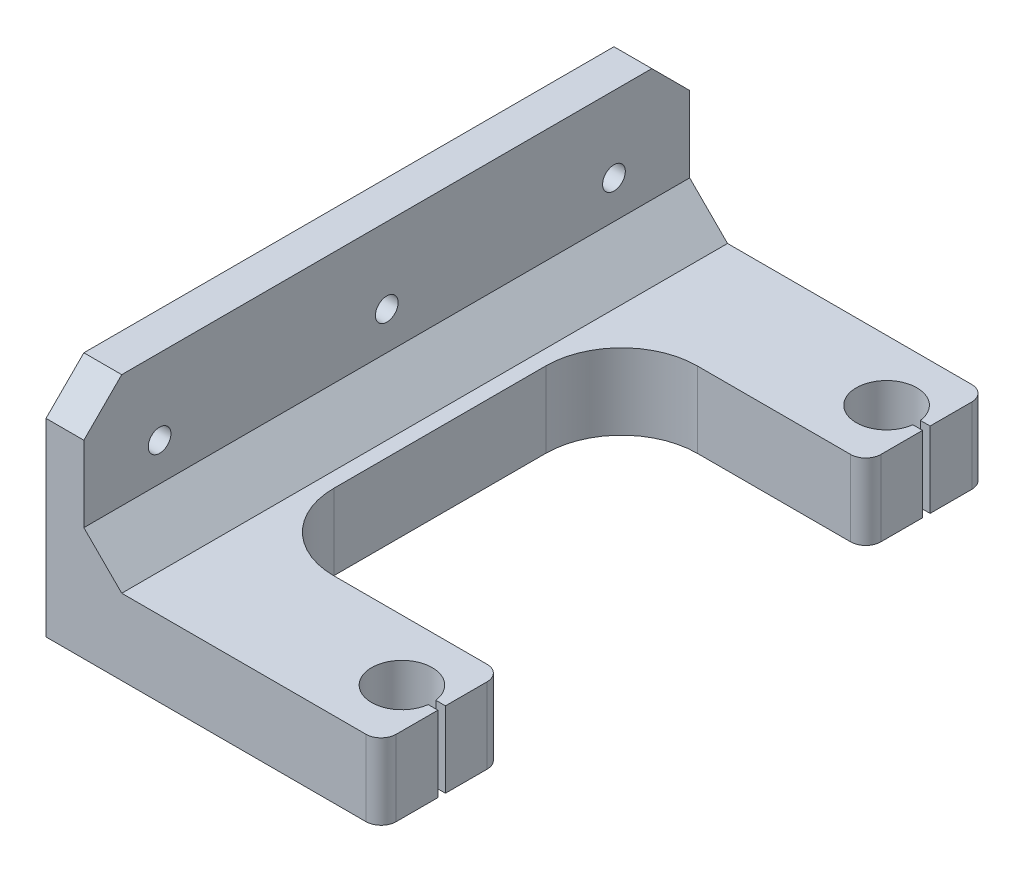
SolidWorks part; units mm, degrees
ref_plane "Front Plane" through (0, 0, 0) normal (0, 0, 1) x (1, 0, 0)
ref_plane "Top Plane" through (0, 0, 0) normal (0, 1, 0) x (1, 0, 0)
ref_plane "Right Plane" through (0, 0, 0) normal (1, 0, 0) x (0, 0, -1)
sketch "Sketch1" plane through (0, 0, 0) normal (0, 1, 0) x (1, 0, 0)
  line L0 (0, 0) -> (0, -80)
  line L1 (0, -80) -> (44.25, -80)
  line L2 (44.25, -80) -> (44.25, -64)
  line L3 (44.25, -64) -> (12, -64)
  line L4 (12, -64) -> (12, -16)
  line L5 (12, -16) -> (44.25, -16)
  line L6 (44.25, -16) -> (44.25, 0)
  line L7 (44.25, 0) -> (0, 0)
  line L8 (0, -40) -> (12, -40) construction
  circle A0 centre (39, -8) radius 4
  circle A1 centre (39, -72) radius 4
  point P15 (22.125, 0)
  dimension "D1" = 8
  dimension "D2" = 32
  dimension "D3" = 39
  dimension "D4" = 16
  dimension "D5" = 5.25
  dimension "D6" = 12
  dimension "D7" = 8
extrude "Boss-Extrude1" add sketch "Sketch1" along normal blind 10
sketch "Sketch2" plane through (0, 10, 0) normal (0, 1, 0) x (1, 0, 0)
  line L0 (44.25, 0) -> (0, 0) construction
  line L1 (0, -80) -> (5, -80)
  line L2 (0, -80) -> (0, 0)
  line L3 (0, 0) -> (5, 0)
  line L4 (5, -80) -> (5, 0)
  dimension "D1" = 5
extrude "Boss-Extrude2" add sketch "Sketch2" along normal blind 20
sketch "Sketch5" plane through (0, 10, 0) normal (0, 1, 0) x (1, 0, 0)
  circle A0 centre (39, -72) radius 4 construction
  circle A1 centre (39, -8) radius 4 construction
  circle A2 centre (39, -72) radius 4
  circle A3 centre (39, -8) radius 4
extrude "Boss-Extrude3" add sketch "Sketch5" along normal blind 2 from surface at -10 starting at face at (25.125, 0, 40)
sketch "Sketch3" plane through (5, 0, 0) normal (1, 0, 0) x (0, 0, -1)
  line L0 (-80, 10) -> (0, 10) construction
  line L1 (-70, 10) -> (-70, 30) construction
  line L2 (-80, 30) -> (0, 30) construction
  line L3 (-80, 30) -> (-80, 10) construction
  line L4 (0, 30) -> (0, 10) construction
  line L5 (-70, 20) -> (-10, 20) construction
  circle A0 centre (-70, 20) radius 1.5
  circle A1 centre (-40, 20) radius 1.5
  circle A2 centre (-10, 20) radius 1.5
  dimension "D1" = 3
  dimension "D2" = 10
  dimension "D3" = 10
extrude "Cut-Extrude1" cut sketch "Sketch3" against normal through all
sketch "Sketch4" plane through (0, 10, 0) normal (0, 1, 0) x (1, 0, 0)
  line L0 (39, -8) -> (44.25, -8) construction
  line L1 (44.25, -16) -> (44.25, 0) construction
  line L2 (39, -7.5) -> (44.25, -7.5)
  line L3 (39, -8.5) -> (44.25, -8.5)
  line L4 (39, -72) -> (44.25, -72) construction
  line L5 (44.25, -80) -> (44.25, -64) construction
  line L6 (39, -71.5) -> (44.25, -71.5)
  line L7 (39, -72.5) -> (44.25, -72.5)
  arc A0 (39, -7.5) -> (39, -8.5) centre (39, -8) ccw
  arc A1 (44.25, -8.5) -> (44.25, -7.5) centre (44.25, -8) ccw
  arc A2 (39, -71.5) -> (39, -72.5) centre (39, -72) ccw
  arc A3 (44.25, -72.5) -> (44.25, -71.5) centre (44.25, -72) ccw
  point P5 (41.625, -8)
  point P10 (41.625, -72)
  dimension "D1" = 1
extrude "Cut-Extrude2" cut sketch "Sketch4" against normal through all
chamfer "Chamfer2" distance 5 angle 45 1 edges at (5, 10, 40)
fillet "Fillet1" radius 2 4 edges at (44.25, 5, 64) (44.25, 5, 80) (44.25, 5, 0) (44.25, 5, 16)
fillet "Fillet2" radius 10 2 edges at (12, 5, 16) (12, 5, 64)
chamfer "Chamfer1" distance 5 angle 45 2 edges at (2.5, 30, 0) (2.5, 30, 80)
